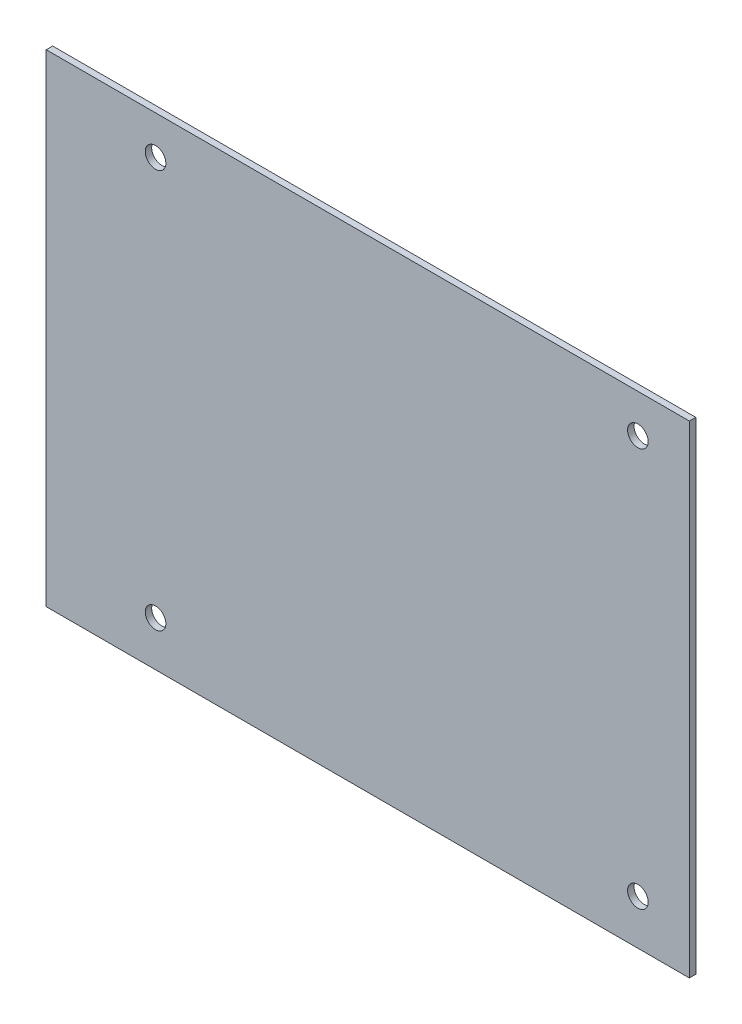
SolidWorks part; units mm, degrees
ref_plane "正面" through (0, 0, 0) normal (0, 0, 1) x (1, 0, 0)
ref_plane "平面" through (0, 0, 0) normal (0, 1, 0) x (1, 0, 0)
ref_plane "右側面" through (0, 0, 0) normal (1, 0, 0) x (0, 0, -1)
sketch "ｽｹｯﾁ1" plane through (0, 0, 0) normal (0, 0, 1) x (1, 0, 0)
  line L1 (-50, 37.5) -> (50, 37.5)
  line L2 (-50, 37.5) -> (-50, -37.5)
  line L3 (-50, -37.5) -> (50, -37.5)
  line L4 (50, 37.5) -> (50, -37.5)
  dimension "D1" = 100
  dimension "D2" = 75
  dimension "D3" = 37.5
  dimension "D4" = 50
extrude "ﾎﾞｽ - 押し出し1" add sketch "ｽｹｯﾁ1" along normal blind 1
sketch "ｽｹｯﾁ2" plane through (0, 0, 1) normal (0, 0, 1) x (1, 0, 0)
  line L0 (-50, -37.5) -> (50, -37.5) construction
  line L2 (50, -37.5) -> (50, 37.5) construction
  circle A0 centre (42, -30.5) radius 1.6
  dimension "D1" = 3.2
  dimension "D2" = 7
  dimension "D3" = 8
extrude "ｶｯﾄ - 押し出し1" cut sketch "ｽｹｯﾁ2" against normal blind 1
pattern_linear "直線ﾊﾟﾀｰﾝ1" count 2 spacing 75 along (-1, 0, 0) count 2 spacing 62 along (0, 1, 0) of "ｶｯﾄ - 押し出し1"
